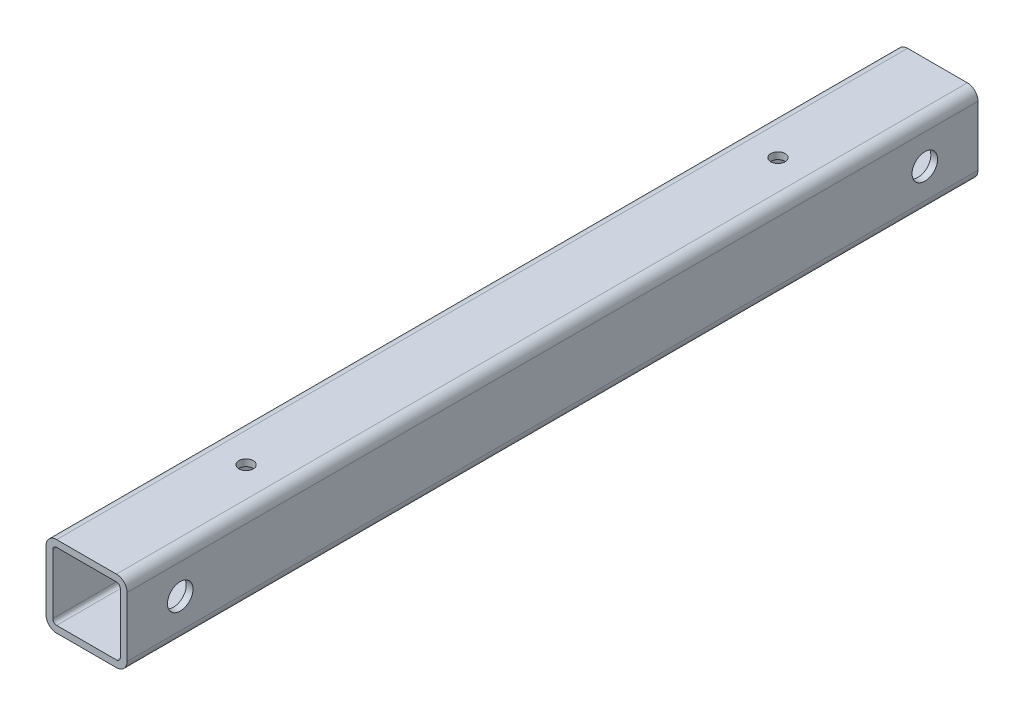
SolidWorks part; units mm, degrees
ref_plane "Front Plane" through (0, 0, 0) normal (0, 0, 1) x (1, 0, 0)
ref_plane "Top Plane" through (0, 0, 0) normal (0, 1, 0) x (1, 0, 0)
ref_plane "Right Plane" through (0, 0, 0) normal (1, 0, 0) x (0, 0, -1)
sketch "Sketch1" plane through (0, 0, 0) normal (0, 0, 1) x (1, 0, 0)
  line L6 (-14.05, 19.05) -> (14.05, 19.05)
  line L7 (19.05, 14.05) -> (19.05, -14.05)
  line L8 (-15.875, 14.05) -> (-15.875, -14.05)
  line L9 (-14.05, -15.875) -> (14.05, -15.875)
  line L10 (14.05, -19.05) -> (-14.05, -19.05)
  line L11 (-19.05, -14.05) -> (-19.05, 14.05)
  line L12 (0, 19.05) -> (0, -19.05) construction
  line L13 (-19.05, 0) -> (19.05, 0) construction
  line L14 (15.875, -14.05) -> (15.875, 14.05)
  line L15 (14.05, 15.875) -> (-14.05, 15.875)
  line L16 (0, 15.875) -> (0, -15.875) construction
  line L17 (-15.875, 0) -> (15.875, 0) construction
  arc A0 (14.05, 19.05) -> (19.05, 14.05) centre (14.05, 14.05) cw
  arc A1 (19.05, -14.05) -> (14.05, -19.05) centre (14.05, -14.05) cw
  arc A2 (-14.05, -19.05) -> (-19.05, -14.05) centre (-14.05, -14.05) cw
  arc A3 (-19.05, 14.05) -> (-14.05, 19.05) centre (-14.05, 14.05) cw
  arc A4 (-15.875, -14.05) -> (-14.05, -15.875) centre (-14.05, -14.05) ccw
  arc A5 (14.05, -15.875) -> (15.875, -14.05) centre (14.05, -14.05) ccw
  arc A6 (15.875, 14.05) -> (14.05, 15.875) centre (14.05, 14.05) ccw
  arc A7 (-14.05, 15.875) -> (-15.875, 14.05) centre (-14.05, 14.05) ccw
  point P40 (0, 0)
  dimension "D3" = 5
  dimension "D4" = 3.175
extrude "Boss-Extrude1" add sketch "Sketch1" along normal blind 400
sketch "Sketch2" plane through (0, 0, 0) normal (1, 0, 0) x (0, 0, -1)
  line L0 (-375, 0) -> (-25, 0) construction
  line L1 (20.955, 0) -> (-20.955, 0) construction
  line L2 (0, 20.955) -> (0, -20.955) construction
  circle A0 centre (-375, 0) radius 6
  circle A1 centre (-25, 0) radius 6
  dimension "D4" = 12
  dimension "D2" = 350
  dimension "D1" = 25
extrude "Cut-Extrude1" cut sketch "Sketch2" against normal through all both and the other way through all
sketch "Sketch3" plane through (0, 0, 0) normal (0, 1, 0) x (1, 0, 0)
  line L0 (0, -325) -> (0, -75) construction
  line L1 (0, -20.955) -> (0, 20.955) construction
  circle A0 centre (0, -325) radius 3.38
  circle A1 centre (0, -75) radius 3.38
  dimension "D4" = 6.76
  dimension "D2" = 250
  dimension "D3" = 75
extrude "Cut-Extrude2" cut sketch "Sketch3" along normal through all both and the other way through all
sketch "Centrepoint" plane through (0, 0, 0) normal (1, 0, 0) x (0, 0, -1)
  point P0 (-200, 0)
  dimension "D1" = 200
equation "\"shovelHoleDiameter\" = 12mm"
equation "\"D4@Sketch2\"=\"shovelHoleDiameter\""
equation "\"mountHoleDiameter\"= 6.76mm"
equation "\"D4@Sketch3\"=\"mountHoleDiameter\""
